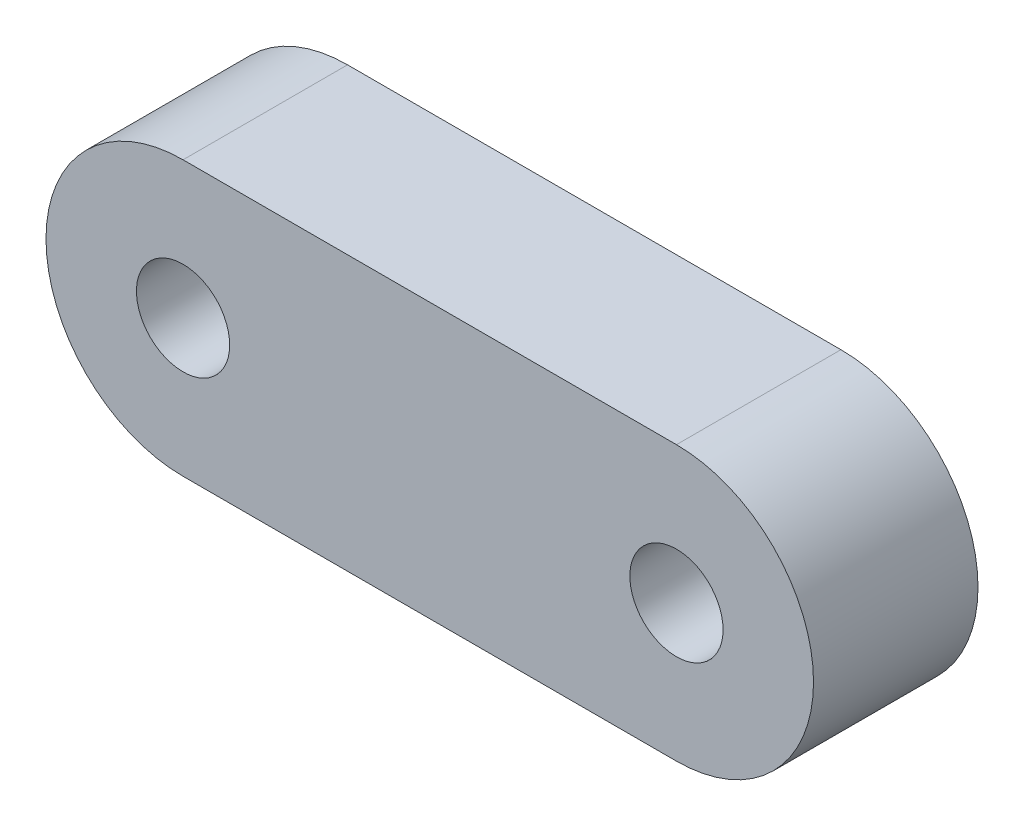
SolidWorks part; units mm, degrees
material "Balsa"
ref_plane "Front Plane" through (0, 0, 0) normal (0, 0, 1) x (1, 0, 0)
ref_plane "Top Plane" through (0, 0, 0) normal (0, 1, 0) x (1, 0, 0)
ref_plane "Right Plane" through (0, 0, 0) normal (1, 0, 0) x (0, 0, -1)
sketch "Sketch2" plane through (0, 0, 0) normal (0, 0, 1) x (1, 0, 0)
  line L0 (7.56, 5) -> (25.56, 5)
  line L1 (7.56, -5) -> (25.56, -5)
  circle A0 centre (7.56, 0) radius 1.7
  circle A1 centre (25.56, 0) radius 1.7
  arc A2 (7.56, 5) -> (7.56, -5) centre (7.56, 0) ccw
  arc A3 (25.56, -5) -> (25.56, 5) centre (25.56, 0) ccw
  dimension "D1" = 18
  dimension "D2" = 3.4
  dimension "D3" = 10
extrude "Boss-Extrude1" add sketch "Sketch2" along normal blind 6
